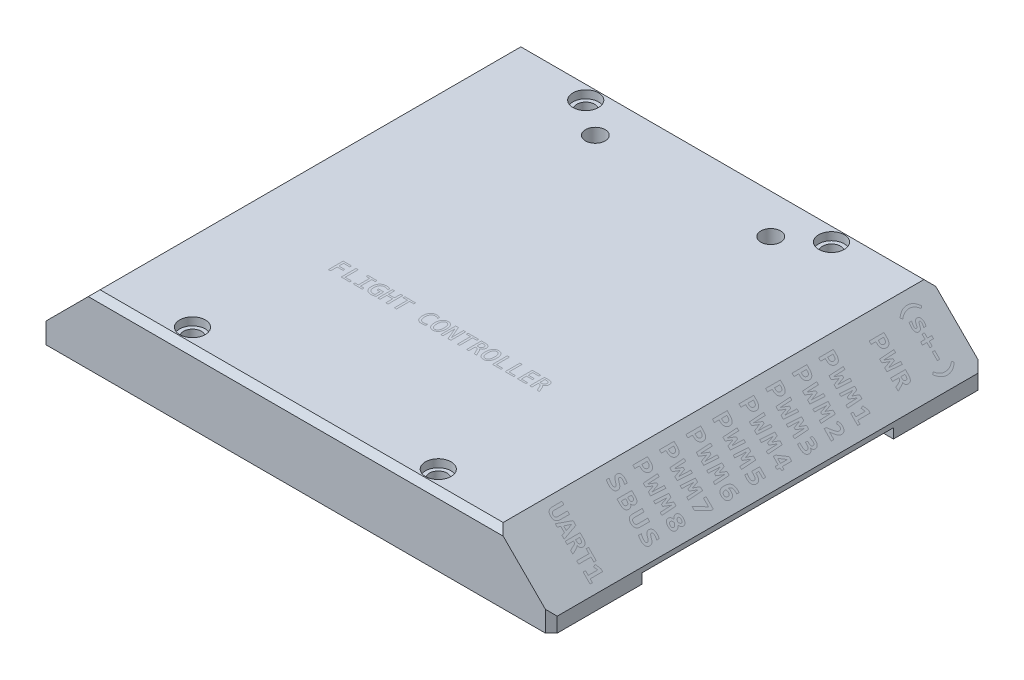
SolidWorks part; units mm, degrees
material "6061-T6 (SS)"
ref_plane "정면" through (0, 0, 0) normal (0, 0, 1) x (1, 0, 0)
ref_plane "윗면" through (0, 0, 0) normal (0, 1, 0) x (1, 0, 0)
ref_plane "우측면" through (0, 0, 0) normal (1, 0, 0) x (0, 0, -1)
ref_plane "평면1" through (0, 7, 0) normal (0, 1, 0) x (1, 0, 0)
sketch "스케치1" plane through (0, 7, 0) normal (0, 1, 0) x (1, 0, 0)
  line L0 (0, 40) -> (0, 0) construction
  line L1 (40, 0) -> (40, 40) construction
  line L2 (0, 40) -> (0, 0) construction
  line L3 (40, 0) -> (40, 40) construction
  line L5 (-6, 42) -> (46, 42)
  line L6 (-6, 42) -> (-6, -2)
  line L7 (-6, -2) -> (46, -2)
  line L8 (46, 42) -> (46, -2)
  dimension "D1" = 2
  dimension "D2" = 2
  dimension "D3" = 6
  dimension "D4" = 6
extrude "보스-돌출1" add sketch "스케치1" against normal up to surface (7 mm away)
sketch "스케치2" plane through (0, 0, 0) normal (0, -1, 0) x (1, 0, 0)
  line L0 (40, 0) -> (40, -40) construction
  line L1 (0, -40) -> (0, 0) construction
  line L2 (40, 0) -> (40, -40) construction
  line L3 (0, -40) -> (0, 0) construction
  line L4 (-0.2, 0.2) -> (-0.2, -40.2)
  line L5 (0, 0) -> (40, 0) construction
  line L6 (0, 0) -> (0, -40) construction
  line L7 (0, -40) -> (40, -40) construction
  line L8 (40, 0) -> (40, -40) construction
  line L9 (-0.2, -40.2) -> (40.2, -40.2)
  line L10 (40.2, 0.2) -> (40.2, -40.2)
  line L11 (-0.2, 0.2) -> (40.2, 0.2)
  dimension "D1" = 0.2
extrude "컷-돌출1" cut sketch "스케치2" against normal blind 5.5
sketch "스케치4" plane through (0, 5.5, 0) normal (0, -1, 0) x (1, 0, 0)
  line L1 (3.34, -5) -> (3.34, -15) construction
  line L3 (2.54, -5) -> (4.14, -5) construction
  line L5 (4.14, -15) -> (2.54, -15) construction
  line L7 (4.64, -5) -> (4.64, -15)
  line L9 (2.04, -5) -> (2.04, -15)
  line L11 (36.66, -5) -> (36.66, -15) construction
  line L13 (35.86, -5) -> (37.46, -5) construction
  line L15 (37.46, -15) -> (35.86, -15) construction
  line L16 (37.96, -5) -> (37.96, -15)
  line L17 (35.36, -5) -> (35.36, -15)
  line L18 (3.34, -25) -> (3.34, -35) construction
  line L19 (2.54, -25) -> (4.14, -25) construction
  line L20 (2.54, -35) -> (4.14, -35) construction
  line L21 (4.64, -25) -> (4.64, -35)
  line L22 (2.04, -25) -> (2.04, -35)
  line L23 (36.66, -35) -> (36.66, -25) construction
  line L24 (37.46, -35) -> (35.86, -35) construction
  line L25 (35.86, -25) -> (37.46, -25) construction
  line L26 (35.36, -35) -> (35.36, -25)
  line L27 (37.96, -35) -> (37.96, -25)
  line L48 (-0.2, -40.2) -> (40.2, -40.2) construction
  line L49 (-0.2, 0.2) -> (6.88, 0.2)
  line L50 (-0.2, 0.2) -> (-0.2, -40.2)
  line L51 (-0.2, -40.2) -> (6.88, -40.2)
  line L52 (6.88, 0.2) -> (6.88, -40.2)
  line L54 (40.2, 0.2) -> (33.12, 0.2)
  line L55 (40.2, 0.2) -> (40.2, -40.2)
  line L56 (40.2, -40.2) -> (33.12, -40.2)
  line L57 (33.12, 0.2) -> (33.12, -40.2)
  arc A0 (4.64, -5) -> (2.04, -5) centre (3.34, -5) ccw
  arc A1 (2.04, -15) -> (4.64, -15) centre (3.34, -15) ccw
  arc A2 (37.96, -5) -> (35.36, -5) centre (36.66, -5) ccw
  arc A3 (35.36, -15) -> (37.96, -15) centre (36.66, -15) ccw
  arc A4 (4.64, -25) -> (2.04, -25) centre (3.34, -25) ccw
  arc A5 (2.04, -35) -> (4.64, -35) centre (3.34, -35) ccw
  arc A6 (35.36, -35) -> (37.96, -35) centre (36.66, -35) ccw
  arc A7 (37.96, -25) -> (35.36, -25) centre (36.66, -25) ccw
  point P6 (3.34, -10)
  point P17 (36.66, -10)
  point P22 (3.34, -30)
  point P45 (36.66, -30)
  dimension "D1" = 1.3
  dimension "D2" = 3.54
  dimension "D3" = 3.54
  dimension "D4" = 3.54
extrude "보스-돌출2" add sketch "스케치4" along normal blind 1
sketch "스케치5" plane through (0, 0, 0) normal (0, -1, 0) x (1, 0, 0)
  line L0 (46, 2) -> (46, -42) construction
  line L1 (46, -7.2) -> (40.2, -7.2)
  line L2 (46, -7.2) -> (46, -32.8)
  line L3 (46, -32.8) -> (40.2, -32.8)
  line L4 (40.2, -7.2) -> (40.2, -32.8)
  line L5 (40.2, -40.2) -> (40.2, 0.2) construction
  line L6 (-0.2, 0.2) -> (-0.2, -40.2) construction
  line L7 (-0.2, -7.2) -> (-6, -7.2)
  line L8 (-0.2, -7.2) -> (-0.2, -32.8)
  line L9 (-0.2, -32.8) -> (-6, -32.8)
  line L10 (-6, -7.2) -> (-6, -32.8)
  line L11 (-6, -42) -> (-6, 2) construction
  line L12 (-6, 2) -> (46, 2) construction
  line L13 (46, -42) -> (-6, -42) construction
  dimension "D1" = 9.2
  dimension "D2" = 9.2
extrude "컷-돌출2" cut sketch "스케치5" against normal blind 1
sketch "스케치7" plane through (0, 5.5, 0) normal (0, -1, 0) x (1, 0, 0)
  line L0 (33.12, 0.2) -> (33.12, -40.2) construction
  line L1 (6.88, -40.2) -> (33.12, -40.2) construction
  line L2 (6.88, -40.2) -> (6.88, 0.2) construction
  circle A0 centre (28.92, -37.4) radius 1
  circle A1 centre (11.08, -37.4) radius 1
  dimension "D1" = 2
  dimension "D2" = 4.2
  dimension "D3" = 2.8
  dimension "D4" = 4.2
extrude "컷-돌출3" cut sketch "스케치7" against normal through all
sketch "스케치13" plane through (0, 0, 0) normal (0, -1, 0) x (1, 0, 0)
  circle A0 centre (7.5, 0) radius 1.75
  circle A1 centre (32.5, 0) radius 1.75
  circle A2 centre (32.5, -40) radius 1.75
  circle A3 centre (7.5, -40) radius 1.75
  dimension "D4" = 3.5
  dimension "D1" = 7.5
  dimension "D2" = 25
  dimension "D3" = 40
extrude "보스-돌출3" add sketch "스케치13" against normal up to next
sketch "스케치9" plane through (0, 7, 0) normal (0, 1, 0) x (1, 0, 0)
  point P0 (7.5, 0)
  point P1 (32.5, 0)
  point P2 (7.5, 40)
  point P3 (32.5, 40)
  point P4 (0, 0)
  dimension "D1" = 7.5
  dimension "D2" = 25
  dimension "D3" = 40
hole_wizard "M1.6 남비 머리 나사용 카운터보어1" positions "스케치10" profile "스케치12" counterbore size "M1.6" standard "ISO" end condition through all
sketch "스케치10" plane through (0, 7, 0) normal (0, 1, 0) x (1, 0, 0)
  point P0 (7.5, 0)
  point P3 (32.5, 0)
  point P6 (7.5, 40)
  point P9 (32.5, 40)
sketch "스케치12" plane through (7.5, 7, 0) normal (1, 0, 0) x (0, 0, 1)
  line L0 (0, 0) -> (0, 7)
  line L1 (0, 7) -> (0.9, 7)
  line L3 (0.9, 7) -> (0.9, 0.8)
  line L4 (0.9, 0.8) -> (1.3, 0.8)
  line L5 (1.3, 0.8) -> (1.3, 0)
  line L7 (1.3, 0) -> (0, 0)
  line L11 (0, -6.35) -> (0, 107.95) construction
  dimension "관통 구멍 지름" = 1.8
  dimension "관통 구멍 깊이" = 7
  dimension "카운터보어 지름" = 2.6
  dimension "카운터보어 깊이" = 0.8
chamfer "모따기1" distance 5.5 angle 45 2 edges at (-6, 7, -20) (46, 7, -20)
sketch "스케치14" plane through (0, 0, 0) normal (0, -1, 0) x (1, 0, 0)
  line L0 (34.2385, 0.2) -> (30.7615, 0.2)
  line L1 (9.2385, 0.2) -> (5.7615, 0.2)
  line L2 (9.2385, -40.2) -> (5.7615, -40.2)
  line L3 (34.2385, -40.2) -> (30.7615, -40.2)
  arc A0 (34.2385, -40.2) -> (30.7615, -40.2) centre (32.5, -40) ccw construction
  arc A1 (9.2385, -40.2) -> (5.7615, -40.2) centre (7.5, -40) ccw construction
  arc A2 (30.7615, 0.2) -> (34.2385, 0.2) centre (32.5, 0) ccw construction
  arc A3 (5.7615, 0.2) -> (9.2385, 0.2) centre (7.5, 0) ccw construction
  arc A4 (34.2385, -40.2) -> (30.7615, -40.2) centre (32.5, -40) ccw
  arc A5 (9.2385, -40.2) -> (5.7615, -40.2) centre (7.5, -40) ccw
  arc A6 (30.7615, 0.2) -> (34.2385, 0.2) centre (32.5, 0) ccw
  arc A7 (5.7615, 0.2) -> (9.2385, 0.2) centre (7.5, 0) ccw
extrude "컷-돌출4" cut sketch "스케치14" against normal blind 1.6
sketch "스케치15" plane through (0, 0, 0) normal (0, -1, 0) x (1, 0, 0)
  line L1 (25, -47.5479) -> (15, -47.5479)
  line L2 (25, -47.5479) -> (25, -34.8344)
  line L3 (25, -34.8344) -> (15, -34.8344)
  line L4 (15, -47.5479) -> (15, -34.8344)
  dimension "D1" = 10
  dimension "D2" = 15
extrude "컷-돌출5" cut sketch "스케치15" against normal blind 5
chamfer "모따기2" distance 0.6 angle 45 6 edges at (20, 7, -42) (20, 7, 2) (-6, 0.75, -42) (-6, 0.75, 2) (46, 0.75, 2) (46, 0.75, -42)
sketch "스케치16" plane through (23.75, 23.75, 0) normal (0.7071, 0.7071, 0) x (0, 0, -1)
  line L0 (34.5188, -31.4663) -> (34.5188, -23.6881) construction
  line L1 (41.4, -31.4663) -> (-1.4, -31.4663) construction
  line L2 (-1.4, -23.6881) -> (41.4, -23.6881) construction
  line L3 (29.9188, -31.4663) -> (29.9188, -23.6881) construction
  line L4 (27.2188, -31.4663) -> (27.2188, -23.6881) construction
  line L5 (24.5188, -31.4663) -> (24.5188, -23.6881) construction
  line L6 (21.8188, -31.4663) -> (21.8188, -23.6881) construction
  line L7 (19.1188, -31.4663) -> (19.1188, -23.6881) construction
  line L8 (16.4188, -31.4663) -> (16.4188, -23.6881) construction
  line L9 (13.7188, -31.4663) -> (13.7188, -23.6881) construction
  line L10 (11.0188, -31.4663) -> (11.0188, -23.6881) construction
  line L11 (8.3188, -31.4663) -> (8.3188, -23.6881) construction
  line L12 (2.5188, -31.4663) -> (2.5188, -23.6881) construction
  line L13 (38.356, -23.6881) -> (38.356, -31.4663) construction
  text T0 "PWR" font "Consolas" height 1.5
  text T1 "PWM1" font "Consolas" height 1.5
  text T2 "PWM2" font "Consolas" height 1.5
  text T3 "PWM3" font "Consolas" height 1.5
  text T4 "PWM4" font "Consolas" height 1.5
  text T5 "PWM5" font "Consolas" height 1.5
  text T6 "PWM6" font "Consolas" height 1.5
  text T7 "PWM7" font "Consolas" height 1.5
  text T8 "PWM8" font "Consolas" height 1.5
  text T9 "SBUS" font "Consolas" height 1.5
  text T10 "UART1" font "Consolas" height 1.5
  text T11 "(s+-)" font "Consolas" height 1.5
  dimension "D1" = 9
sketch "스케치17" plane through (-3.75, 3.75, 0) normal (-0.7071, 0.7071, 0) x (0, 0, 1)
  line L0 (-2.649, 4.5962) -> (-2.649, -3.182) construction
  line L1 (-41.4, 4.5962) -> (1.4, 4.5962) construction
  line L2 (1.4, -3.182) -> (-41.4, -3.182) construction
  line L3 (-8.5017, 4.5962) -> (-8.5017, -3.182) construction
  line L4 (-11.2017, 4.5962) -> (-11.2017, -3.182) construction
  line L5 (-13.9017, 4.5962) -> (-13.9017, -3.182) construction
  line L6 (-16.6017, 4.5962) -> (-16.6017, -3.182) construction
  line L7 (-19.3017, 4.5962) -> (-19.3017, -3.182) construction
  line L8 (-22.0017, 4.5962) -> (-22.0017, -3.182) construction
  line L9 (-24.7017, 4.5962) -> (-24.7017, -3.182) construction
  line L10 (-27.4017, 4.5962) -> (-27.4017, -3.182) construction
  line L11 (-30.1017, 4.5962) -> (-30.1017, -3.182) construction
  line L12 (-34.6545, 4.5962) -> (-34.6545, -3.182) construction
  line L13 (-38.5624, -3.182) -> (-38.5624, 4.5962) construction
  text T0 "UART2" font "Consolas" height 1.5
  text T1 "UART3" font "Consolas" height 1.5
  text T2 "(-+s)" font "Consolas" height 1.5
  text T3 "PWM09" font "Consolas" height 1.5
  text T4 "PWM10" font "Consolas" height 1.5
  text T5 "PWM11" font "Consolas" height 1.5
  text T6 "PWM12" font "Consolas" height 1.5
  text T7 "PWM13" font "Consolas" height 1.5
  text T8 "PWM14" font "Consolas" height 1.5
  text T9 "PWM15" font "Consolas" height 1.5
  text T10 "PWM16" font "Consolas" height 1.5
  text T11 "UART6TX" font "Consolas" height 1.5
  dimension "D1" = 9
sketch "스케치18" plane through (0, 7, 0) normal (0, 1, 0) x (1, 0, 0)
  line L0 (6.9251, 21.2135) -> (33.0749, 21.2135) construction
  line L1 (-5.4, -2) -> (45.4, -2) construction
  line L2 (6.9251, 11.9891) -> (33.0749, 11.9891) construction
  line L3 (6.9251, 5.5088) -> (33.0749, 5.5088) construction
  text T1 "FLIGHT CONTROLLER" font "Consolas" height 1.5
  point P3 (20, 21.2135)
  point P6 (20, -2)
fillet "필렛1" radius 1 12 edges at (34.2385, 3.05, 0.2) (5.7615, 3.05, 0.2) (6.88, 5, -1.6365) (-0.2, 2.25, 0.2) (33.12, 5, -1.6365) (40.2, 2.25, 0.2) (5.7615, 3.05, -40.2) (34.2385, 3.05, -40.2) (40.2, 2.25, -40.2) (33.12, 5, -38.3635) (6.88, 5, -38.3635) (-0.2, 2.25, -40.2)
sketch "스케치19" plane through (0, 0, 0) normal (0, -1, 0) x (1, 0, 0)
  line L0 (0.8, -40.2) -> (6.6225, -40.2) construction
  line L1 (-0.2, -32.8) -> (-0.2, -39.2) construction
  line L2 (33.3775, -40.2) -> (39.2, -40.2) construction
  line L3 (40.2, -39.2) -> (40.2, -32.8) construction
  line L4 (40.2, -7.2) -> (40.2, -0.8) construction
  line L5 (39.2, 0.2) -> (33.3775, 0.2) construction
  line L6 (6.6225, 0.2) -> (0.8, 0.2) construction
  line L7 (-0.2, -0.8) -> (-0.2, -7.2) construction
  line L8 (-0.2, -40.2) -> (6.6225, -40.2) construction
  line L9 (-0.2, -32.8) -> (-0.2, -40.2) construction
  line L10 (33.3775, -40.2) -> (40.2, -40.2) construction
  line L11 (40.2, -40.2) -> (40.2, -32.8) construction
  line L12 (40.2, -7.2) -> (40.2, 0.2) construction
  line L13 (40.2, 0.2) -> (33.3775, 0.2) construction
  line L14 (6.6225, 0.2) -> (-0.2, 0.2) construction
  line L15 (-0.2, 0.2) -> (-0.2, -7.2) construction
  circle A0 centre (-0.2, -40.2) radius 0.9
  circle A1 centre (-0.2, 0.2) radius 0.9
  circle A2 centre (40.2, 0.2) radius 0.9
  circle A3 centre (40.2, -40.2) radius 0.9
  dimension "D1" = 1.8
extrude "컷-돌출9" cut sketch "스케치19" against normal blind 1.6
split line "분할선1"
split line "분할선2"
split line "분할선3"
equation "\"D1@스케치1\"=\"D2@스케치1\""
equation "\"D4@스케치1\"=\"D3@스케치1\""
equation "\"D4@스케치7\"=\"D2@스케치7\""
equation "\"D3@스케치4\"=\"D2@스케치4\""
equation "\"D4@스케치4\"=\"D2@스케치4\""
